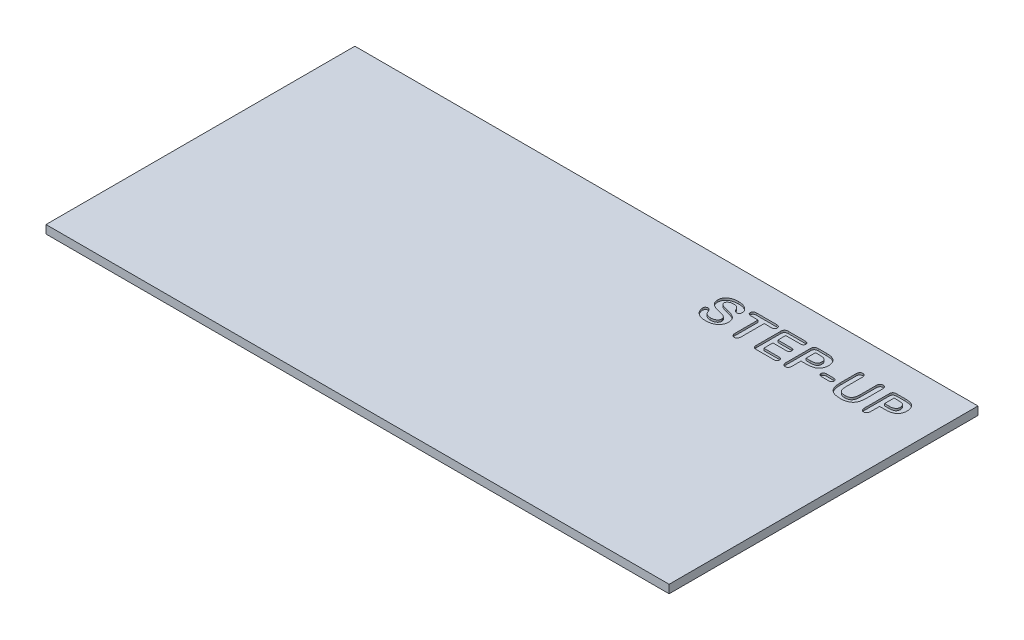
SolidWorks part; units mm, degrees
ref_plane "Front Plane" through (0, 0, 0) normal (0, 0, 1) x (1, 0, 0)
ref_plane "Top Plane" through (0, 0, 0) normal (0, 1, 0) x (1, 0, 0)
ref_plane "Right Plane" through (0, 0, 0) normal (1, 0, 0) x (0, 0, -1)
sketch "Sketch1" plane through (0, 0, 0) normal (0, 1, 0) x (1, 0, 0)
  line L5 (-75.35, 37.35) -> (75.35, 37.35)
  line L6 (-75.35, 37.35) -> (-75.35, -37.35)
  line L7 (-75.35, -37.35) -> (75.35, -37.35)
  line L8 (75.35, 37.35) -> (75.35, -37.35)
  line L9 (-75.35, 37.35) -> (75.35, -37.35) construction
  line L10 (-75.35, -37.35) -> (75.35, 37.35) construction
  point P0 (0, 0)
  dimension "D1" = 150.7
  dimension "D2" = 74.7
extrude "Boss-Extrude1" add sketch "Sketch1" along normal blind 2
sketch "Sketch2" plane through (0, 2, 0) normal (0, 1, 0) x (1, 0, 0)
  line L0 (-75.35, 37.35) -> (-75.35, -37.35) construction
  line L1 (-75.35, 30.35) -> (68.35, 30.35) construction
  line L2 (-75.35, 30.35) -> (-75.35, 22.35) construction
  line L3 (-75.35, 22.35) -> (68.35, 22.35) construction
  line L4 (68.35, 30.35) -> (68.35, 22.35) construction
  line L6 (75.35, -37.35) -> (75.35, 37.35) construction
  line L7 (75.35, 37.35) -> (-75.35, 37.35) construction
  text T0 "STEP-UP" font "Arial Rounded MT Bold" height 8
  dimension "D1" = 8
  dimension "D2" = 7
  dimension "D3" = 7
extrude "Cut-Extrude1" cut sketch "Sketch2" against normal blind 0.5
